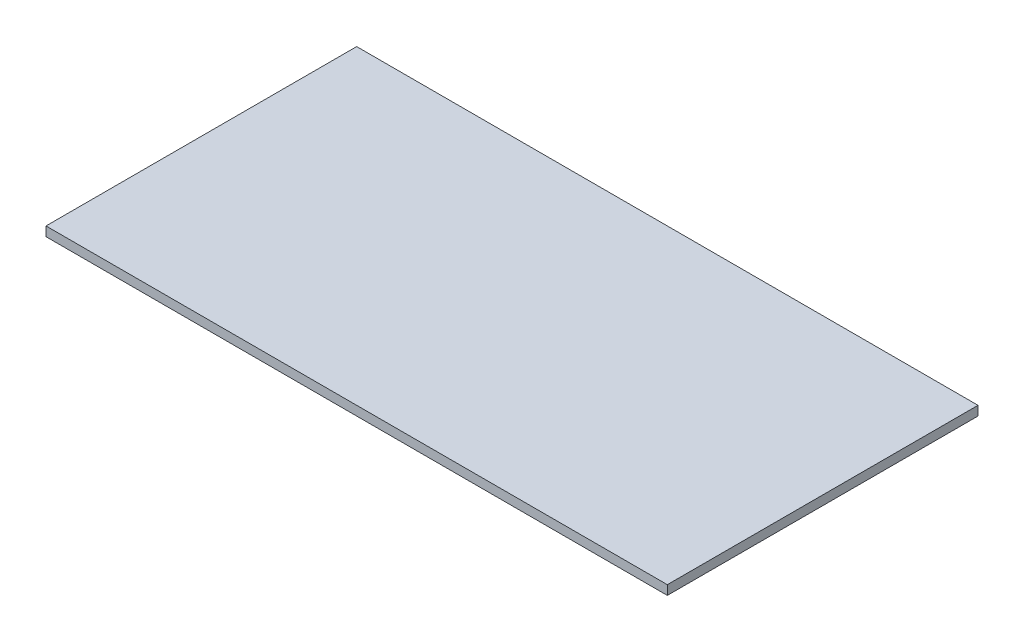
SolidWorks part; units mm, degrees
material "Cedar"
ref_plane "Front Plane" through (0, 0, 0) normal (0, 0, 1) x (1, 0, 0)
ref_plane "Top Plane" through (0, 0, 0) normal (0, 1, 0) x (1, 0, 0)
ref_plane "Right Plane" through (0, 0, 0) normal (1, 0, 0) x (0, 0, -1)
sketch "Sketch1" plane through (0, 0, 0) normal (0, 1, 0) x (1, 0, 0)
  line L1 (700, -350) -> (-700, -350)
  line L2 (700, -350) -> (700, 350)
  line L3 (700, 350) -> (-700, 350)
  line L4 (-700, -350) -> (-700, 350)
  line L5 (700, -350) -> (-700, 350) construction
  line L6 (700, 350) -> (-700, -350) construction
  point P0 (0, 0)
  dimension "D1" = 700
  dimension "D2" = 1400
extrude "Boss-Extrude1" add sketch "Sketch1" along normal blind 21
